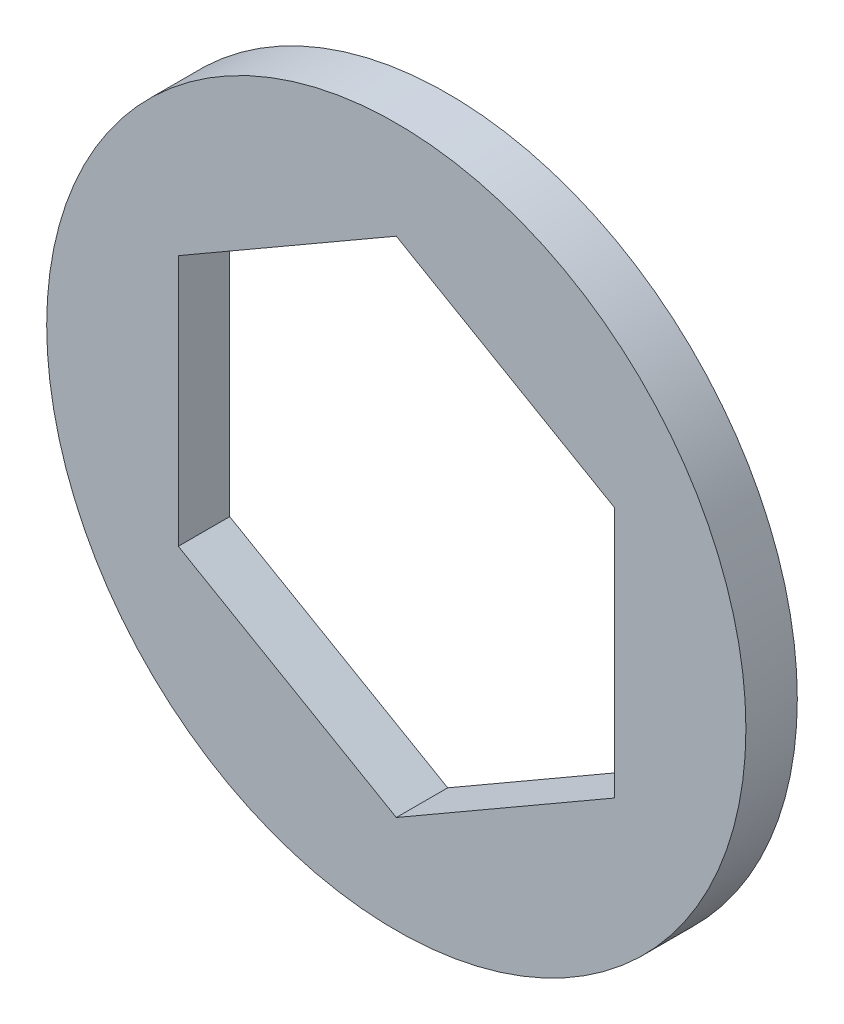
SolidWorks part; units mm, degrees
material "Nylon 101"
ref_plane "Front Plane" through (0, 0, 0) normal (0, 0, 1) x (1, 0, 0)
ref_plane "Top Plane" through (0, 0, 0) normal (0, 1, 0) x (1, 0, 0)
ref_plane "Right Plane" through (0, 0, 0) normal (1, 0, 0) x (0, 0, -1)
sketch "Sketch1" plane through (0, 0, 0) normal (0, 0, 1) x (1, 0, 0)
  line L1 (0, 7.7723) -> (-6.731, 3.8861)
  line L2 (-6.731, 3.8861) -> (-6.731, -3.8861)
  line L3 (-6.731, -3.8861) -> (0, -7.7723)
  line L4 (0, -7.7723) -> (6.731, -3.8861)
  line L5 (6.731, -3.8861) -> (6.731, 3.8861)
  line L6 (6.731, 3.8861) -> (0, 7.7723)
  circle A0 centre (0, 0) radius 6.731 construction
  circle A1 centre (0, 0) radius 10.795
  dimension "D1" = 13.462
  dimension "D2" = 21.59
extrude "Boss-Extrude1" add sketch "Sketch1" along normal blind 1.5875
